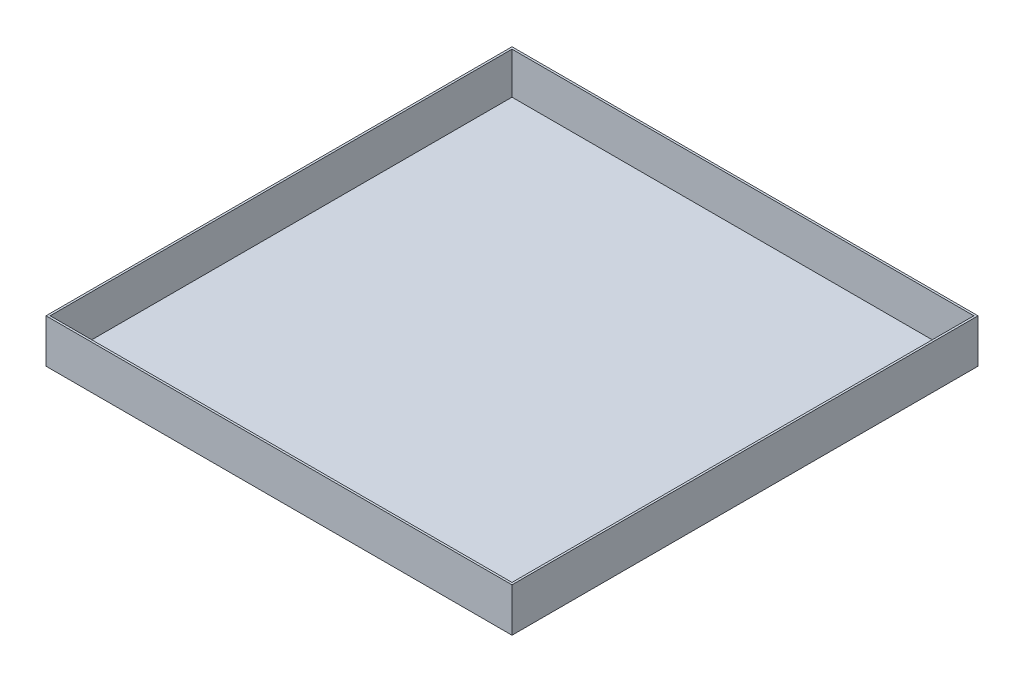
SolidWorks part; units mm, degrees
ref_plane "Front" through (0, 0, 0) normal (0, 0, 1) x (1, 0, 0)
ref_plane "Top" through (0, 0, 0) normal (0, 1, 0) x (1, 0, 0)
ref_plane "Right" through (0, 0, 0) normal (1, 0, 0) x (0, 0, -1)
sketch "Croquis1" plane through (0, 0, 0) normal (0, 1, 0) x (1, 0, 0)
  line L1 (-112, 112) -> (112, 112)
  line L2 (-112, 112) -> (-112, -112)
  line L3 (-112, -112) -> (112, -112)
  line L4 (112, 112) -> (112, -112)
  line L5 (-112, 112) -> (112, -112) construction
  line L6 (-112, -112) -> (112, 112) construction
  point P0 (0, 0)
  dimension "D1" = 224
  dimension "D2" = 224
extrude "Saliente-Extruir1" add sketch "Croquis1" along normal blind 1
sketch "Croquis3" plane through (0, 1, 0) normal (0, 1, 0) x (1, 0, 0)
  line L0 (-112, -112) -> (112, -112) construction
  line L2 (112, 112) -> (112, -112)
  line L3 (112, -112) -> (-112, -112)
  line L4 (-112, 112) -> (-112, -112)
  line L5 (112, 112) -> (-112, -112) construction
  line L6 (112, -112) -> (-112, 112) construction
  line L8 (112, 112) -> (-112, 112)
  line L9 (112, 112) -> (112, -112)
  line L10 (112, -112) -> (-112, -112)
  line L11 (-112, 112) -> (-112, -112)
  line L12 (112, 112) -> (-112, -112) construction
  line L13 (112, -112) -> (-112, 112) construction
  line L14 (111, 111) -> (-111, 111)
  line L15 (111, 111) -> (111, -111)
  line L16 (111, -111) -> (-111, -111)
  line L17 (-111, 111) -> (-111, -111)
  line L18 (111, 111) -> (-111, -111) construction
  line L19 (111, -111) -> (-111, 111) construction
  point P0 (0, 0)
  point P8 (0, 0)
  point P9 (0, 0)
  line M1 (112, -112) -> (112, 112)
  line M2 (112, 112) -> (-112, 112)
  line M3 (-112, 112) -> (-112, -112)
  line M4 (-112, -112) -> (112, -112)
  dimension "D1" = 224
  dimension "D2" = 222
extrude "Saliente-Extruir2" add sketch "Croquis3" along normal blind 20 contours L17 L14 L15 L16 M4 M1 M2 M3
